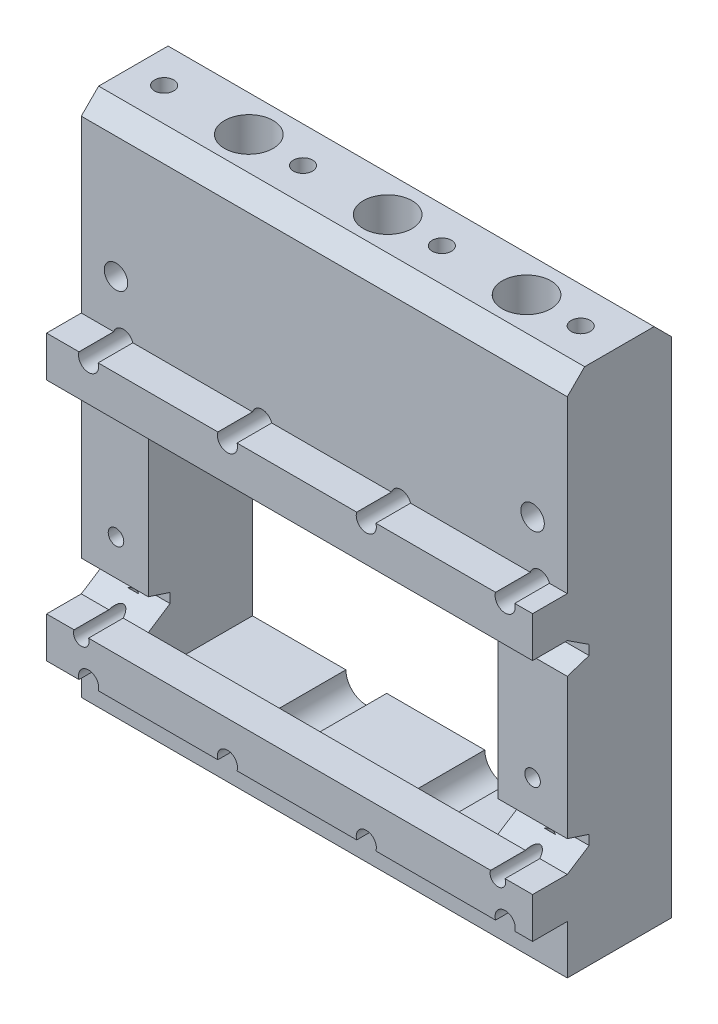
SolidWorks part; units mm, degrees
ref_plane "Front Plane" through (0, 0, 0) normal (0, 0, 1) x (1, 0, 0)
ref_plane "Top Plane" through (0, 0, 0) normal (0, 1, 0) x (1, 0, 0)
ref_plane "Right Plane" through (0, 0, 0) normal (1, 0, 0) x (0, 0, -1)
sketch "Sketch1" plane through (0, 0, 0) normal (0, 0, 1) x (1, 0, 0)
  line L1 (-63.1034, 106.2931) -> (76.8966, 106.2931)
  line L2 (-63.1034, 106.2931) -> (-63.1034, -43.7069)
  line L3 (-63.1034, -43.7069) -> (76.8966, -43.7069)
  line L4 (76.8966, 106.2931) -> (76.8966, -43.7069)
  line L5 (-43.7931, 31.2931) -> (56.8966, 31.2931)
  line L6 (-43.7931, 31.2931) -> (-43.7931, -28.7069)
  line L7 (-43.7931, -28.7069) -> (56.8966, -28.7069)
  line L8 (56.8966, 31.2931) -> (56.8966, -28.7069)
  dimension "D1" = 60
  dimension "D2" = 150
  dimension "D3" = 75
  dimension "D4" = 140
  dimension "D5" = 20
extrude "Boss-Extrude1" add sketch "Sketch1" along normal blind 30
sketch "Sketch2" plane through (-63.1034, 0, 0) normal (-1, 0, 0) x (0, 0, 1)
  line L0 (30, 40.4671) -> (23.72, 36.3783)
  line L1 (30, 106.2931) -> (30, -43.7069) construction
  line L2 (23.72, 36.3783) -> (23.72, 33.5887)
  line L3 (23.72, 33.5887) -> (30, 31.5444)
  line L4 (30, 31.5444) -> (30, 40.4671)
extrude "Cut-Extrude1" cut sketch "Sketch2" against normal blind 300
ref_plane "Plane1" through (0, 11.2931, 0) normal (0, -1, 0) x (-1, 0, 0)
ref_plane "Plane2" through (0, 46.2931, 0) normal (0, 1, 0) x (1, 0, 0)
sketch "Sketch11" plane through (0, 0, 30) normal (0, 0, 1) x (1, 0, 0)
  line L0 (-63.1034, 106.2931) -> (-63.1034, 40.4671) construction
  line L1 (-63.1034, 52.1826) -> (76.8966, 52.1826)
  line L2 (-63.1034, 52.1826) -> (-63.1034, 40.4671)
  line L3 (-63.1034, 40.4671) -> (76.8966, 40.4671)
  line L4 (76.8966, 52.1826) -> (76.8966, 40.4671)
  line L5 (76.8966, 40.4671) -> (76.8966, 106.2931) construction
extrude "Boss-Extrude2" add sketch "Sketch11" along normal blind 10
mirror "Mirror1" about plane through (0, 11.2931, 0) normal (0, -1, 0) of "Boss-Extrude2", "Cut-Extrude1"
sketch "Sketch3" plane through (0, 106.2931, 0) normal (0, 1, 0) x (1, 0, 0)
  circle A0 centre (-29.4046, -15.4362) radius 3
extrude "Cut-Extrude2" cut sketch "Sketch3" against normal blind 100
sketch "Sketch4" plane through (0, 106.2931, 0) normal (0, 1, 0) x (1, 0, 0)
  circle A0 centre (-29.4046, -15.4362) radius 7
  circle A1 centre (-29.4046, -15.4362) radius 3 construction
extrude "Cut-Extrude3" cut sketch "Sketch4" against normal blind 70
pattern_linear "LPattern1" count 3 spacing 40 along (1, 0, 0) of "Cut-Extrude2", "Cut-Extrude3"
sketch "Sketch5" plane through (0, 0, 0) normal (0, 0, -1) x (-1, 0, 0)
  line L0 (63.1034, 106.2931) -> (63.1034, -43.7069) construction
  line L1 (43.7931, -28.7069) -> (-56.8966, -28.7069) construction
  circle A0 centre (53.1034, -18.7069) radius 2.2387
  dimension "D1" = 10
  dimension "D2" = 10
extrude "Cut-Extrude4" cut sketch "Sketch5" against normal blind 100
sketch "Sketch6" plane through (0, 0, 0) normal (0, 0, -1) x (-1, 0, 0)
  circle A0 centre (53.1034, -18.7069) radius 4.369
extrude "Cut-Extrude5" cut sketch "Sketch6" against normal blind 25
pattern_linear "LPattern2" count 2 spacing 20 along (0, 1, 0) count 2 spacing 120 along (1, 0, 0) of "Cut-Extrude4", "Cut-Extrude5"
sketch "Sketch7" plane through (0, 0, 0) normal (0, 0, -1) x (-1, 0, 0)
  line L0 (-56.8966, 31.2931) -> (43.7931, 31.2931) construction
  circle A0 centre (51.0031, 51.2931) radius 2.9002
  dimension "D1" = 20
extrude "Cut-Extrude6" cut sketch "Sketch7" against normal blind 40
sketch "Sketch8" plane through (0, 0, 0) normal (0, 0, -1) x (-1, 0, 0)
  circle A0 centre (51.0031, 51.2931) radius 5.871
extrude "Cut-Extrude7" cut sketch "Sketch8" against normal blind 25
pattern_linear "LPattern3" count 4 spacing 40 along (1, 0, 0) count 2 spacing 80 along (0, -1, 0) of "Cut-Extrude6", "Cut-Extrude7"
sketch "Sketch9" plane through (0, 0, 0) normal (0, 0, -1) x (-1, 0, 0)
  line L0 (-76.8966, -43.7069) -> (-76.8966, 106.2931) construction
  line L1 (-76.8966, 106.2931) -> (63.1034, 106.2931) construction
  circle A0 centre (-66.8966, 66.2931) radius 3.3818
  dimension "D1" = 10
  dimension "D2" = 40
extrude "Cut-Extrude8" cut sketch "Sketch9" against normal blind 100
sketch "Sketch10" plane through (0, 0, 30) normal (0, 0, 1) x (1, 0, 0)
  circle A0 centre (66.8966, 66.2931) radius 6.9825
  circle A1 centre (66.8966, 66.2931) radius 3.3818 construction
extrude "Cut-Extrude9" cut sketch "Sketch10" against normal blind 20 from offset 10 offset against normal yes
pattern_linear "LPattern4" count 2 spacing 120 along (-1, 0, 0) of "Cut-Extrude9", "Cut-Extrude8"
chamfer "Chamfer1" distance 5 angle 45 2 edges at (6.8966, 106.2931, 0) (6.8966, 106.2931, 30)
sketch "Sketch16" plane through (0, 0, 0) normal (0, 0, -1) x (-1, 0, 0)
  line L1 (-59.4867, 87.6307) -> (-72.521, 87.6307)
  line L2 (-59.4867, 87.6307) -> (-59.4867, 98.6235)
  line L3 (-59.4867, 98.6235) -> (-72.521, 98.6235)
  line L4 (-72.521, 87.6307) -> (-72.521, 98.6235)
extrude "Cut-Extrude13" cut sketch "Sketch16" against normal blind 20
sketch "Sketch17" plane through (0, 106.2931, 0) normal (0, 1, 0) x (1, 0, 0)
  circle A0 centre (66.1626, -15.3982) radius 2.7657
extrude "Cut-Extrude14" cut sketch "Sketch17" against normal blind 15
pattern_linear "LPattern6" count 4 spacing 40 along (-1, 0, 0) of "Cut-Extrude13", "Cut-Extrude14"
